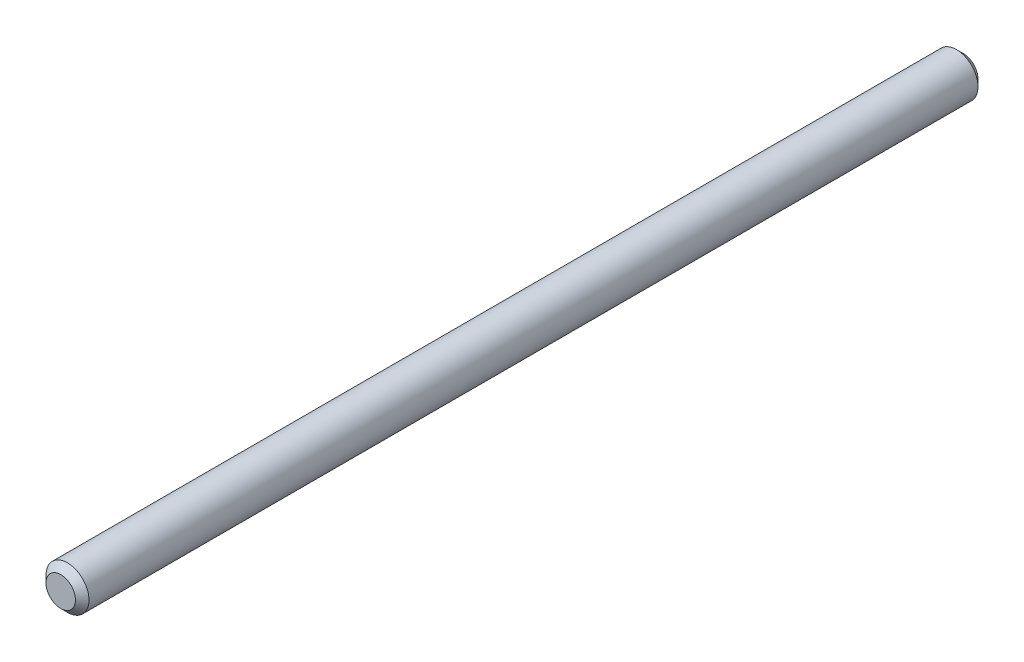
SolidWorks part; units mm, degrees
ref_plane "Alzado" through (0, 0, 0) normal (0, 0, 1) x (1, 0, 0)
ref_plane "Planta" through (0, 0, 0) normal (0, 1, 0) x (1, 0, 0)
ref_plane "Vista lateral" through (0, 0, 0) normal (1, 0, 0) x (0, 0, -1)
sketch "Croquis1" plane through (0, 0, 0) normal (0, 0, 1) x (1, 0, 0)
  circle A0 centre (0, 0) radius 4.7625
  dimension "D1" = 9.525
extrude "Saliente-Extruir1" add sketch "Croquis1" along normal mid plane 200
chamfer "Chaflán1" distance 1.5 angle 45 2 edges at (4.7625, 0, -100) (4.7625, 0, 100)
